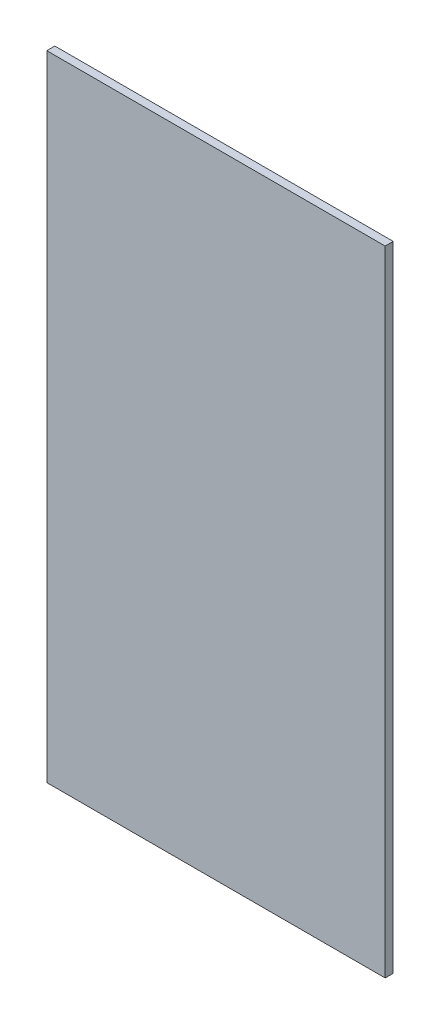
SolidWorks part; units mm, degrees
ref_plane "Front Plane" through (0, 0, 0) normal (0, 0, 1) x (1, 0, 0)
ref_plane "Top Plane" through (0, 0, 0) normal (0, 1, 0) x (1, 0, 0)
ref_plane "Right Plane" through (0, 0, 0) normal (1, 0, 0) x (0, 0, -1)
sketch "Sketch1" plane through (0, 0, 0) normal (0, 0, 1) x (1, 0, 0)
  line L1 (61.5, 116.5) -> (-1.5, 116.5)
  line L2 (61.5, 116.5) -> (61.5, -1.5)
  line L3 (61.5, -1.5) -> (-1.5, -1.5)
  line L4 (-1.5, 116.5) -> (-1.5, -1.5)
extrude "Boss-Extrude1" add sketch "Sketch1" along normal blind 1.5
